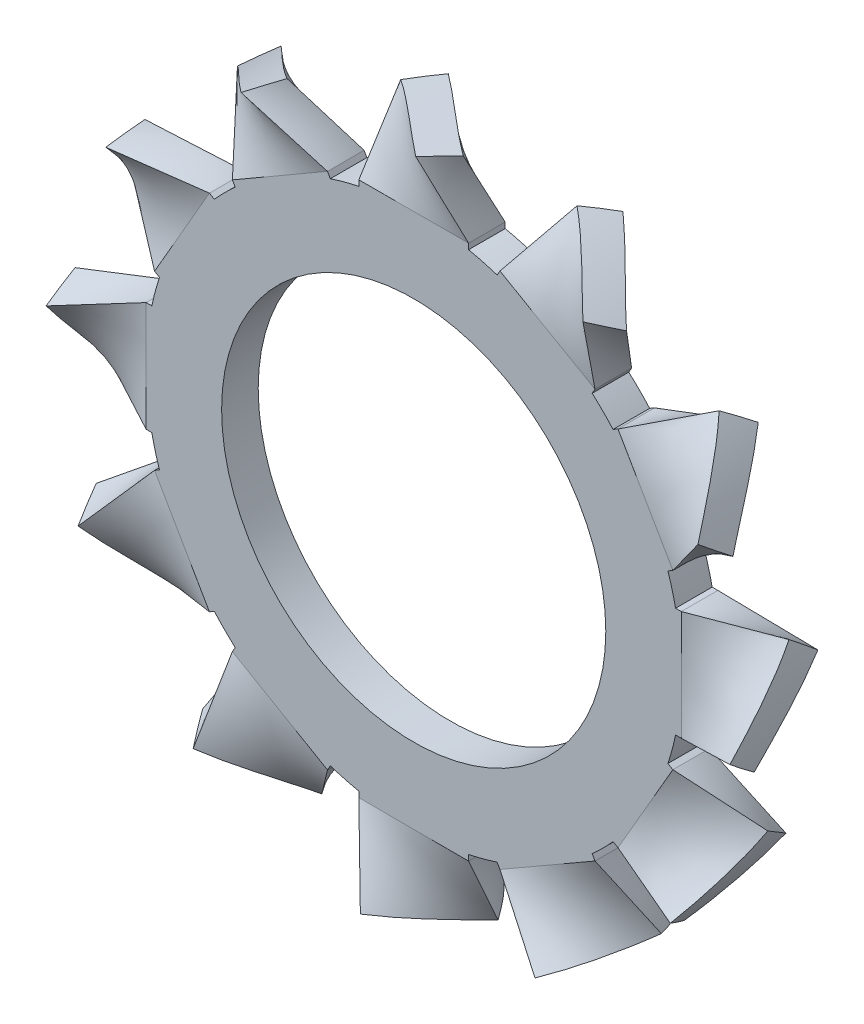
SolidWorks part; units mm, degrees
ref_plane "Front Plane" through (0, 0, 0) normal (0, 0, 1) x (1, 0, 0)
ref_plane "Top Plane" through (0, 0, 0) normal (0, 1, 0) x (1, 0, 0)
ref_plane "Right Plane" through (0, 0, 0) normal (1, 0, 0) x (0, 0, -1)
sketch "Sketch1" plane through (0, 0, 0) normal (0, 0, 1) x (1, 0, 0)
  line L0 (0, 0) -> (0, 7.5) construction
  line L1 (4.2, 0) -> (7.5, 0) construction
  circle A0 centre (0, 0) radius 4.2
  circle A1 centre (0, 0) radius 7.5
  circle A2 centre (0, 0) radius 5.85
  point P4 (0, 4.2)
  point P9 (5.85, 0)
  point P10 (0, 5.85)
  point P11 (0, -5.85)
  dimension "OD" = 15
  dimension "ID" = 8.4
ref_plane "Plane1" through (0, 5.85, 0) normal (0, 1, 0) x (-1, 0, 0)
sketch "Sketch2" plane through (0, 5.85, 0) normal (0, 1, 0) x (-1, 0, 0)
  line L0 (-1.2, 0) -> (1.2, 0) construction
  line L1 (-1.2, 0.4) -> (1.2, 0.4)
  line L2 (-1.2, 0.4) -> (-1.2, -0.4)
  line L3 (-1.2, -0.4) -> (1.2, -0.4)
  line L4 (1.2, 0.4) -> (1.2, -0.4)
  dimension "D1" = 2.4
ref_plane "Plane2" through (0, 7.5, 0) normal (0, 1, 0) x (-1, 0, 0)
sketch "Sketch3" plane through (0, 7.5, 0) normal (0, 1, 0) x (-1, 0, 0)
  line L0 (0, 0) -> (0.8273, -0.6942) construction
  line L1 (1.0587, -0.4184) -> (0.5959, -0.97)
  line L2 (1.0587, -0.4184) -> (-0.5959, 0.97)
  line L3 (0.5959, -0.97) -> (-1.0587, 0.4184)
  line L4 (-0.5959, 0.97) -> (-1.0587, 0.4184)
  line L5 (5.85, 0) -> (-5.85, 0) construction
  line L6 (0, 0) -> (0.2314, 0.2758) construction
  dimension "D1" = 40
  dimension "D2" = 0.72
  dimension "D3" = 2.16
loft "Loft1" add profiles "Sketch3", "Sketch2"
sketch "Sketch4" plane through (0, 5.85, 0) normal (0, -1, 0) x (1, 0, 0)
  line L4 (1.2, -0.4) -> (1.2, 0.4)
  line L5 (1.2, 0.4) -> (-1.2, 0.4)
  line L6 (-1.2, 0.4) -> (-1.2, -0.4)
  line L7 (-1.2, -0.4) -> (1.2, -0.4)
  line L8 (1.2, -0.4) -> (1.2, 0.4)
  line L9 (1.2, 0.4) -> (-1.2, 0.4)
  line L10 (-1.2, 0.4) -> (-1.2, -0.4)
  line L11 (-1.2, -0.4) -> (1.2, -0.4)
  dimension "D1" = 0
extrude "Extrude1" add sketch "Sketch4" along normal up to vertex (1.65 mm away) up to point (0, 4.2, 0)
ref_axis "Axis1" through (0, 0, -0.6066) along (0, 0, 1)
pattern_circular "CirPattern1" count 12 over 360 about axis through (0, 0, -0.6066) along (0, 0, 1) of bodies 102
sketch "Sketch5" plane through (0, 0, 0) normal (0, 0, 1) x (1, 0, 0)
  circle A0 centre (0, 0) radius 5.85 construction
  circle A1 centre (0, 0) radius 4.2 construction
  circle A2 centre (0, 0) radius 5.85
  circle A3 centre (0, 0) radius 4.2
extrude "Extrude2" add sketch "Sketch5" along normal up to vertex (0.4 mm away) and the other way up to vertex (0.4 mm away) up to point (-1.2, 4.2, 0.4) other way up to point (-1.2, 4.2, -0.4)
sketch "Sketch6" plane through (0, 0, 0) normal (0, 0, 1) x (1, 0, 0)
  circle A0 centre (0, 0) radius 7.5 construction
  circle A1 centre (0, 0) radius 7.5
extrude "Cut-Extrude1" cut sketch "Sketch6" against normal through all and the other way through all flip side to cut
sketch "Sketch7" plane through (0, 0, 0) normal (1, 0, 0) x (0, 0, -1)
  line L0 (0.4, -5.85) -> (-0.4, -5.85) construction
  line L1 (0.4, -4.2) -> (0.4, 4.2) construction
equation "\"D1@Sketch2\" = \"height@Sketch2\" * 3"
equation "\"D2@Sketch3\" = \"height@Sketch2\" * 0.9"
equation "\"D3@Sketch3\" = \"D2@Sketch3\" * 3"
